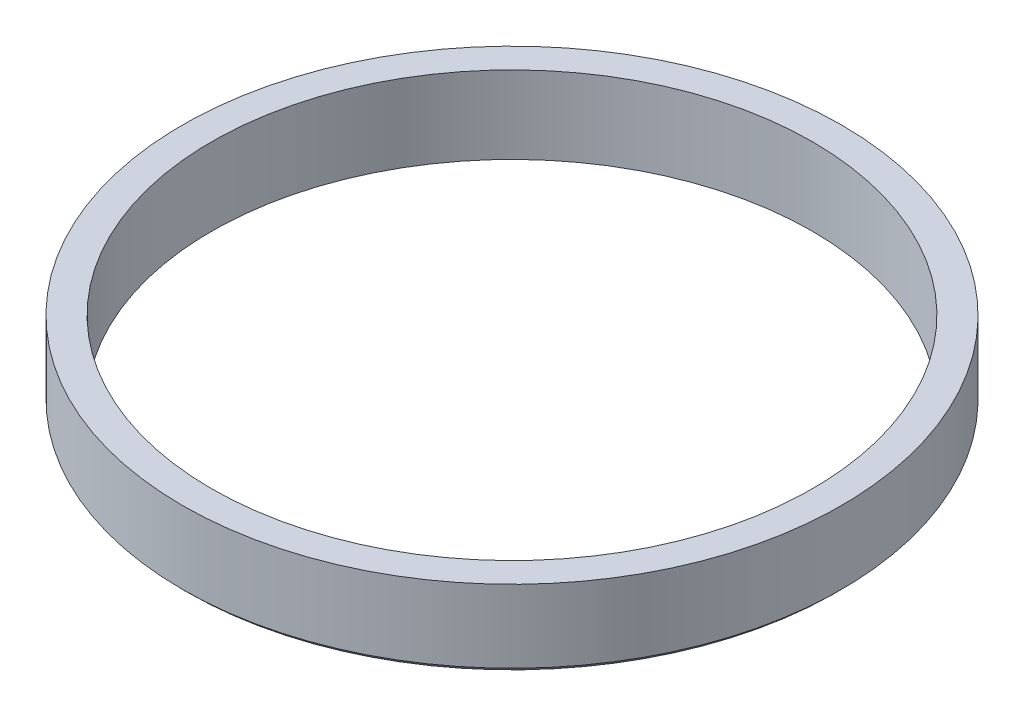
SolidWorks part; units mm, degrees
material "6061-T6 (SS)"
ref_plane "Piano frontale" through (0, 0, 0) normal (0, 0, 1) x (1, 0, 0)
ref_plane "Piano superiore" through (0, 0, 0) normal (0, 1, 0) x (1, 0, 0)
ref_plane "Piano destro" through (0, 0, 0) normal (1, 0, 0) x (0, 0, -1)
sketch "Schizzo1" plane through (0, 0, 0) normal (0, 0, 1) x (1, 0, 0)
  line L0 (0, 0) -> (0, 71.1819) construction
  line L1 (-62, 0) -> (-68, 0)
  line L2 (-68, 0) -> (-68, 16)
  line L3 (-68, 16) -> (-62, 16)
  line L4 (-62, 16) -> (-62, 0)
  dimension "D1" = 124
  dimension "D2" = 136
  dimension "D3" = 16
revolve "Rivoluzione1" add sketch "Schizzo1" angle 360 about L0
chamfer "Smusso1" distance 1 angle 45 1 edges at (0, 0, -68)
